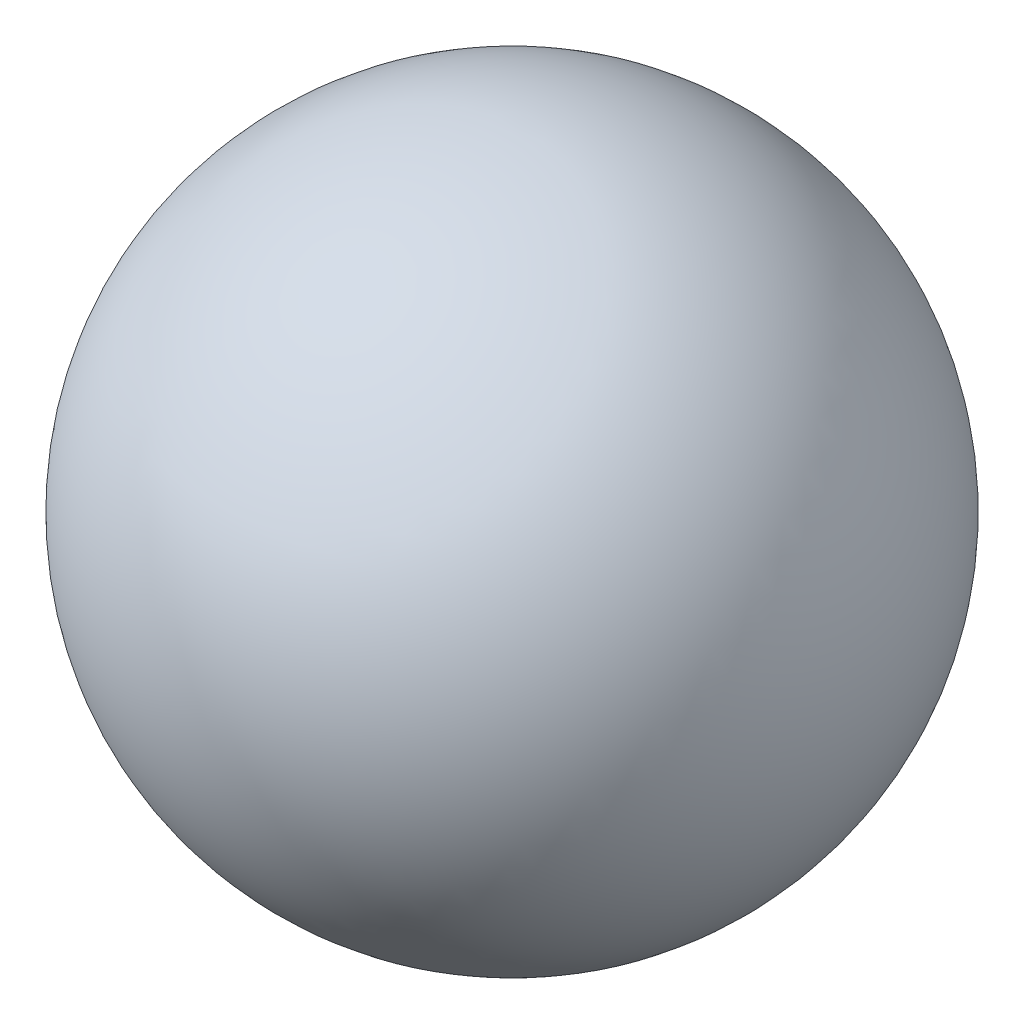
SolidWorks part; units mm, degrees
material "合金钢"
ref_plane "前视基准面" through (0, 0, 0) normal (0, 0, 1) x (1, 0, 0)
ref_plane "上视基准面" through (0, 0, 0) normal (0, 1, 0) x (1, 0, 0)
ref_plane "右视基准面" through (0, 0, 0) normal (1, 0, 0) x (0, 0, -1)
sketch "草图1" plane through (0, 0, 0) normal (0, 0, 1) x (1, 0, 0)
  line L0 (0, 59.062) -> (0, -51.3402) construction
  line L1 (73.75, 23.4563) -> (73.75, -23.4563) construction
  line L2 (73.75, 17.5) -> (73.75, -17.5)
  arc A0 (73.75, -17.5) -> (73.75, 17.5) centre (73.75, 0) ccw
  dimension "D1" = 73.75
  dimension "D2" = 35
revolve "旋转1" add sketch "草图1" angle 360 about L1
